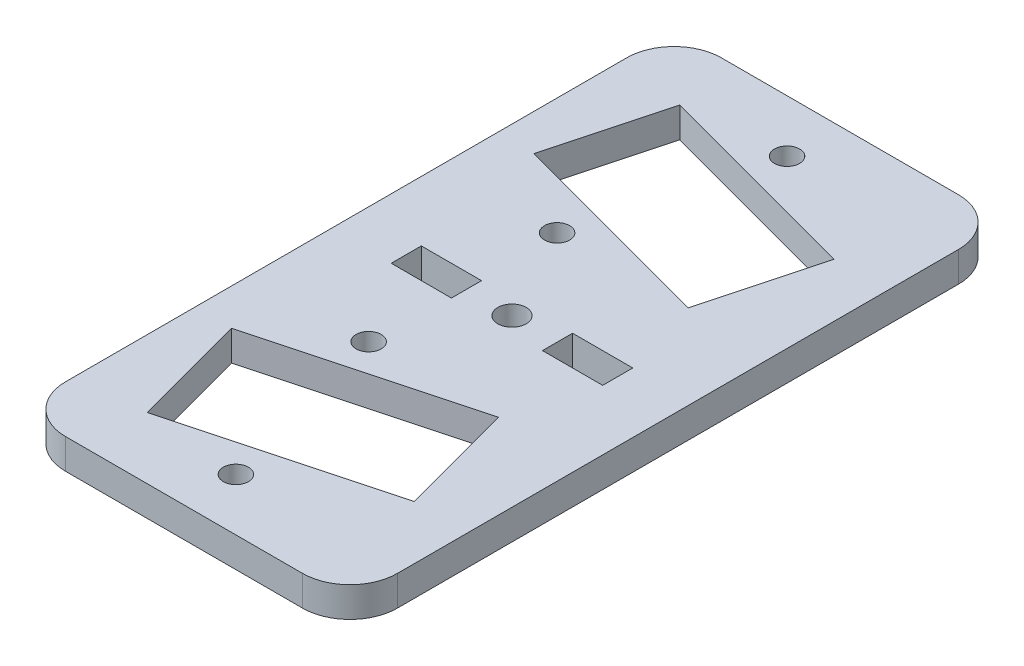
SolidWorks part; units mm, degrees
ref_plane "Front Plane" through (0, 0, 0) normal (0, 0, 1) x (1, 0, 0)
ref_plane "Top Plane" through (0, 0, 0) normal (0, 1, 0) x (1, 0, 0)
ref_plane "Right Plane" through (0, 0, 0) normal (1, 0, 0) x (0, 0, -1)
sketch "Sketch1" plane through (0, 0, 0) normal (0, 1, 0) x (1, 0, 0)
  line L0 (240.7757, 11.1461) -> (262.992, 5.1932)
  line L1 (241.9075, 29.7812) -> (266.9075, 29.7812)
  line L2 (236.9075, 24.7812) -> (236.9075, -34.3947)
  line L3 (241.9075, -39.3947) -> (266.9075, -39.3947)
  line L4 (271.9075, 24.7812) -> (271.9075, -34.3947)
  line L5 (240.7757, 11.1461) -> (244.0251, 23.2731)
  line L6 (262.992, 5.1932) -> (266.2414, 17.3202)
  line L7 (244.0251, 23.2731) -> (266.2414, 17.3202)
  line L8 (253.0712, 24.5996) -> (255.6305, 23.9137) construction
  line L9 (252.1737, 16.1327) -> (251.4878, 13.5732) construction
  line L10 (242.4004, 17.2096) -> (264.6167, 11.2567) construction
  line L11 (236.9075, -4.8068) -> (271.9075, -4.8068) construction
  line L12 (242.4004, -26.8231) -> (264.6167, -20.8703) construction
  line L13 (252.1737, -25.7463) -> (251.4878, -23.1868) construction
  line L14 (253.0712, -34.2132) -> (255.6305, -33.5273) construction
  line L15 (262.992, -14.8068) -> (266.2414, -26.9338)
  line L16 (240.7757, -20.7596) -> (262.992, -14.8068)
  line L17 (244.0251, -32.8866) -> (240.7757, -20.7596)
  line L18 (266.2414, -26.9338) -> (244.0251, -32.8866)
  line L20 (243.2575, -6.3943) -> (249.6075, -6.3943)
  line L21 (243.2575, -6.3943) -> (243.2575, -3.2193)
  line L22 (243.2575, -3.2193) -> (249.6075, -3.2193)
  line L23 (249.6075, -6.3943) -> (249.6075, -3.2193)
  line L24 (243.2575, -6.3943) -> (249.6075, -3.2193) construction
  line L25 (243.2575, -3.2193) -> (249.6075, -6.3943) construction
  line L26 (259.2075, -6.3943) -> (265.5575, -6.3943)
  line L27 (259.2075, -6.3943) -> (259.2075, -3.2193)
  line L28 (259.2075, -3.2193) -> (265.5575, -3.2193)
  line L29 (265.5575, -6.3943) -> (265.5575, -3.2193)
  line L30 (259.2075, -6.3943) -> (265.5575, -3.2193) construction
  line L31 (259.2075, -3.2193) -> (265.5575, -6.3943) construction
  circle A0 centre (254.3509, 24.2567) radius 1.3248
  circle A1 centre (249.2262, 5.1313) radius 1.3248
  circle A2 centre (249.2262, -14.7449) radius 1.3248
  circle A3 centre (254.3509, -33.8702) radius 1.3248
  circle A4 centre (254.4075, -4.8068) radius 1.5
  arc A5 (236.9075, -34.3947) -> (241.9075, -39.3947) centre (241.9075, -34.3947) ccw
  arc A6 (266.9075, -39.3947) -> (271.9075, -34.3947) centre (266.9075, -34.3947) ccw
  arc A7 (266.9075, 29.7812) -> (271.9075, 24.7812) centre (266.9075, 24.7812) cw
  arc A8 (241.9075, 29.7812) -> (236.9075, 24.7812) centre (241.9075, 24.7812) ccw
  point P26 (246.4325, -4.8068)
  point P31 (262.3825, -4.8068)
  point P44 (271.9075, 29.7812)
  point P47 (236.9075, 29.7812)
  dimension "D10" = 3
  dimension "D11" = 5
  dimension "D12" = 19.8
  dimension "D1" = 10
  dimension "D2" = 3.175
  dimension "D3" = 3.175
  dimension "D4" = 6.35
  dimension "D5" = 6.35
  dimension "D6" = 6.35
  dimension "D7" = 9.6
  dimension "D8" = 35
  dimension "D9" = 6.35
extrude "Boss-Extrude1" add sketch "Sketch1" along normal blind 3.175
